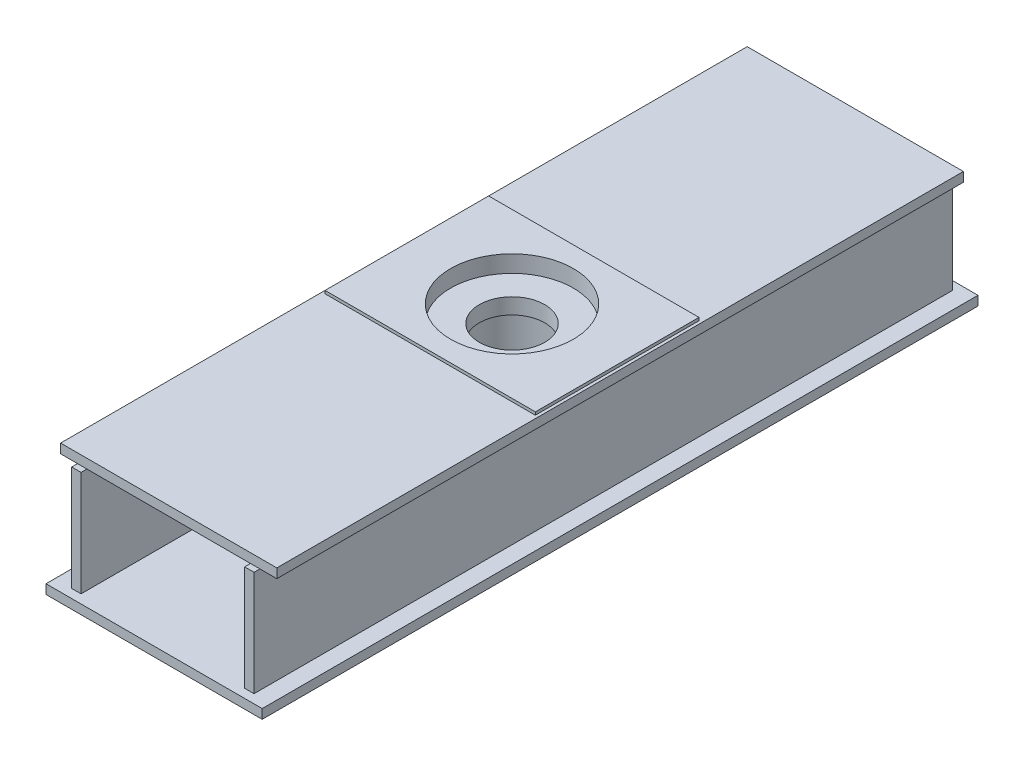
SolidWorks part; units mm, degrees
ref_plane "前视基准面" through (0, 0, 0) normal (0, 0, 1) x (1, 0, 0)
ref_plane "上视基准面" through (0, 0, 0) normal (0, 1, 0) x (1, 0, 0)
ref_plane "右视基准面" through (0, 0, 0) normal (1, 0, 0) x (0, 0, -1)
sketch "草图1" plane through (0, 0, 0) normal (0, 1, 0) x (0, 0, -1)
  line L0 (-994.2562, 0) -> (49005.7438, 0) construction
  line L1 (-612.5, 185) -> (612.5, 185)
  line L2 (-612.5, 185) -> (-612.5, -185)
  line L3 (-612.5, -185) -> (612.5, -185)
  line L4 (612.5, 185) -> (612.5, -185)
  line L5 (0, -1000) -> (0, 49000) construction
  dimension "D1" = 370
  dimension "D2" = 1225
extrude "凸台-拉伸1" add sketch "草图1" along normal blind 16
sketch "草图2" plane through (0, 16, 0) normal (0, 1, 0) x (1, 0, 0)
  line L1 (-140, 140) -> (140, 140)
  line L2 (-140, 140) -> (-140, -140)
  line L3 (-140, -140) -> (140, -140)
  line L4 (140, 140) -> (140, -140)
  dimension "D1" = 280
  dimension "D2" = 140
  dimension "D3" = 140
extrude "凸台-拉伸2" add sketch "草图2" along normal blind 10
sketch "草图3" plane through (0, 26, 0) normal (0, 1, 0) x (1, 0, 0)
  circle A0 centre (0, 0) radius 75
  circle A1 centre (0, 0) radius 85
  dimension "D1" = 170
  dimension "D2" = 150
extrude "凸台-拉伸3" add sketch "草图3" along normal blind 135
sketch "草图4" plane through (0, 26, 0) normal (0, 1, 0) x (1, 0, 0)
  line L0 (0, 0) -> (4327.4957, 10447.4989) construction
  line L1 (0, -1000) -> (0, 49000) construction
  line L2 (27.8524, 80.3072) -> (52.5775, 139.999)
  line L3 (52.5775, 139.999) -> (61.8163, 136.1722)
  line L4 (61.8163, 136.1722) -> (37.0912, 76.4804)
  line L6 (140, 140) -> (-140, 140) construction
  circle A0 centre (0, 0) radius 85 construction
  arc A1 (27.8524, 80.3072) -> (37.0912, 76.4804) centre (0, 0) cw
  dimension "D1" = 10
  dimension "D2" = 0.001
  dimension "D3" = 22.5
extrude "凸台-拉伸4" add sketch "草图4" along normal blind 135
pattern_circular "阵列(圆周)1" count 8 over 360 about axis through (0, 0, 0) along (0, 1, 0) of "凸台-拉伸4"
sketch "草图5" plane through (0, 161, 0) normal (0, 1, 0) x (1, 0, 0)
  line L0 (-1000, 0) -> (49000, 0) construction
  line L1 (-140, 140) -> (140, 140)
  line L2 (-140, 140) -> (-140, -140)
  line L3 (-140, -140) -> (140, -140)
  line L4 (140, 140) -> (140, -140)
  line L5 (0, -1000) -> (0, 49000) construction
  circle A0 centre (0, 0) radius 56
  dimension "D3" = 112
  dimension "D1" = 280
  dimension "D2" = 280
extrude "凸台-拉伸5" add sketch "草图5" along normal blind 35
sketch "草图6" plane through (0, 196, 0) normal (0, 1, 0) x (1, 0, 0)
  circle A0 centre (0, 0) radius 105
  dimension "D1" = 210
extrude "切除-拉伸1" cut sketch "草图6" against normal blind 8
sketch "草图7" plane through (0, 16, 0) normal (0, 1, 0) x (1, 0, 0)
  line L0 (-1000, 0) -> (49000, 0) construction
  line L1 (-140, 597.5) -> (-156, 597.5)
  line L2 (-140, 597.5) -> (-140, -597.5)
  line L3 (-140, -597.5) -> (-156, -597.5)
  line L4 (-156, 597.5) -> (-156, -597.5)
  line L5 (140, 597.5) -> (156, 597.5)
  line L6 (140, 597.5) -> (140, -597.5)
  line L7 (140, -597.5) -> (156, -597.5)
  line L8 (156, 597.5) -> (156, -597.5)
  line L10 (-140, 140) -> (-140, -140) construction
  line L11 (140, -140) -> (140, 140) construction
  dimension "D1" = 1195
  dimension "D2" = 16
extrude "凸台-拉伸8" add sketch "草图7" along normal blind 180
sketch "草图8" plane through (0, 196, 0) normal (0, 1, 0) x (1, 0, 0)
  line L0 (-1000, 0) -> (49000, 0) construction
  line L1 (-185, 587.5) -> (185, 587.5)
  line L2 (-185, 587.5) -> (-185, -587.5)
  line L3 (-185, -587.5) -> (185, -587.5)
  line L4 (185, 587.5) -> (185, -587.5)
  line L5 (0, -1000) -> (0, 49000) construction
  circle A0 centre (0, 0) radius 105
  circle A1 centre (0, 0) radius 105 construction
  dimension "D1" = 370
  dimension "D2" = 1175
extrude "凸台-拉伸9" add sketch "草图8" along normal blind 16
sketch "草图9" plane through (0, 212, 0) normal (0, 1, 0) x (1, 0, 0)
  line L0 (-1000, 0) -> (49000, 0) construction
  line L1 (0, -1000) -> (0, 49000) construction
  line L3 (-180, 140) -> (180, 140)
  line L4 (-180, 140) -> (-180, -140)
  line L5 (-180, -140) -> (180, -140)
  line L6 (180, 140) -> (180, -140)
  circle A0 centre (0, 0) radius 105
  circle A1 centre (0, 0) radius 105 construction
  dimension "D1" = 360
  dimension "D2" = 280
extrude "凸台-拉伸10" add sketch "草图9" along normal blind 5
